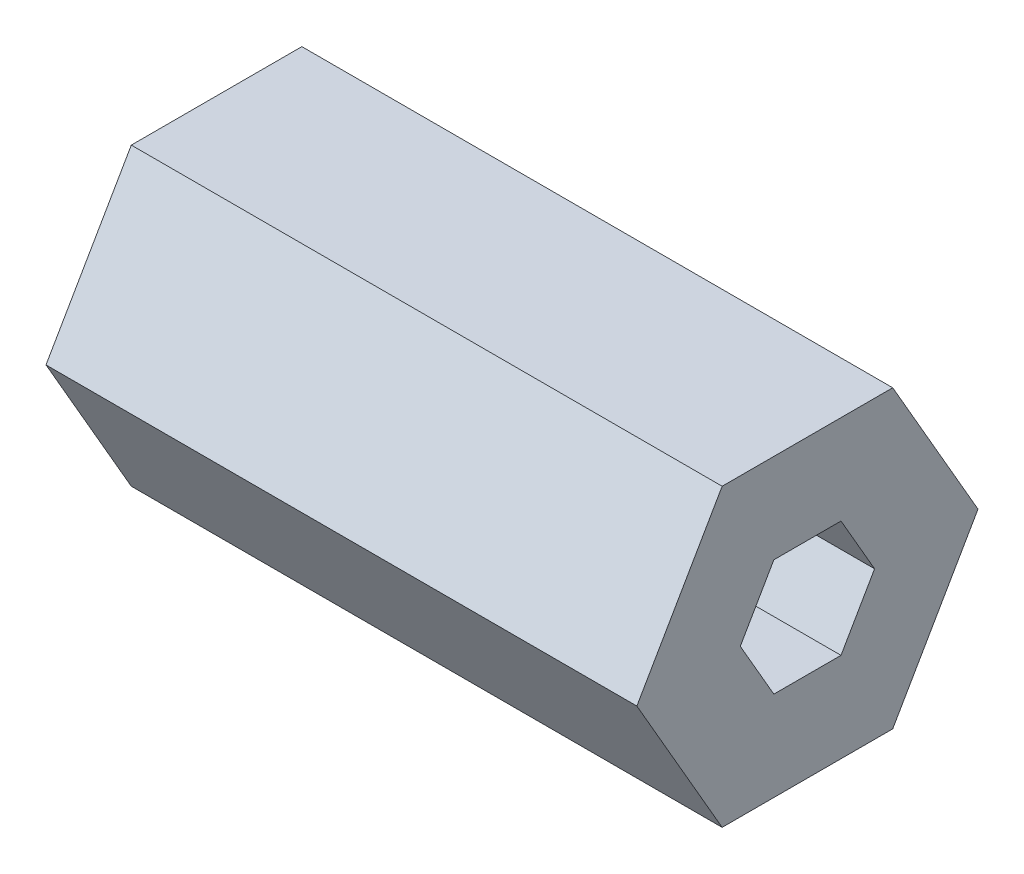
SolidWorks part; units mm, degrees
ref_plane "Front" through (0, 0, 0) normal (0, 0, 1) x (1, 0, 0)
ref_plane "Top" through (0, 0, 0) normal (0, 1, 0) x (1, 0, 0)
ref_plane "Right" through (0, 0, 0) normal (1, 0, 0) x (0, 0, -1)
sketch "Sketch1" plane through (0, 0, 0) normal (1, 0, 0) x (0, 0, -1)
  line L1 (2.8868, 0) -> (1.4434, 2.5)
  line L2 (1.4434, 2.5) -> (-1.4434, 2.5)
  line L3 (-1.4434, 2.5) -> (-2.8868, 0)
  line L4 (-2.8868, 0) -> (-1.4434, -2.5)
  line L5 (-1.4434, -2.5) -> (1.4434, -2.5)
  line L6 (1.4434, -2.5) -> (2.8868, 0)
  line L7 (7.3323, 0) -> (3.6662, 6.35)
  line L8 (3.6662, 6.35) -> (-3.6662, 6.35)
  line L9 (-3.6662, 6.35) -> (-7.3323, 0)
  line L10 (-7.3323, 0) -> (-3.6662, -6.35)
  line L11 (-3.6662, -6.35) -> (3.6662, -6.35)
  line L12 (3.6662, -6.35) -> (7.3323, 0)
  circle A0 centre (0, 0) radius 2.5 construction
  circle A1 centre (0, 0) radius 6.35 construction
  dimension "D1" = 12.7
  dimension "D2" = 5
extrude "Boss-Extrude1" add sketch "Sketch1" along normal mid plane 25.4
